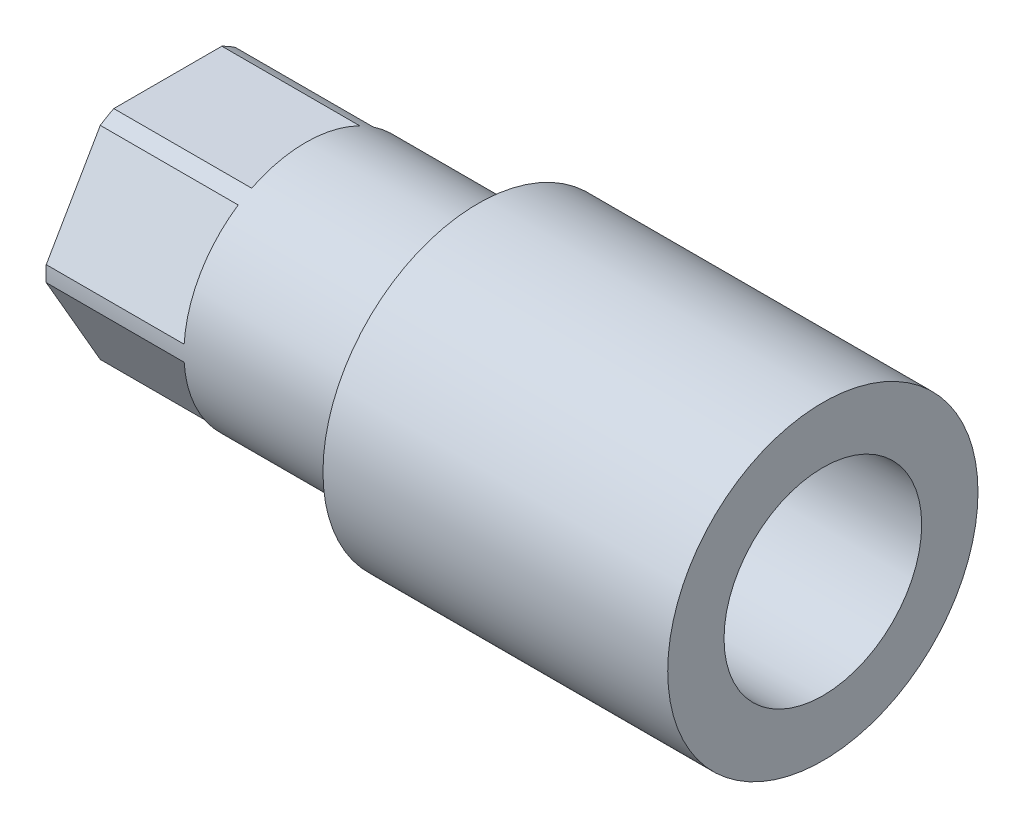
SolidWorks part; units mm, degrees
material "A286, generico"
ref_plane "Front Plane" through (0, 0, 0) normal (0, 0, 1) x (1, 0, 0)
ref_plane "Top Plane" through (0, 0, 0) normal (0, 1, 0) x (1, 0, 0)
ref_plane "Right Plane" through (0, 0, 0) normal (1, 0, 0) x (0, 0, -1)
sketch "Sketch1" plane through (0, 0, 0) normal (0, 0, 1) x (1, 0, 0)
  line L2 (57, -13.5) -> (27, -13.5)
  line L3 (27, -13.5) -> (27, -10.6)
  line L6 (27, -10.6) -> (0, -10.6)
  line L7 (0, -10.6) -> (0, -3.175)
  line L8 (0, 0) -> (57, 0) construction
  line L9 (0, -3.175) -> (34, -3.175)
  line L10 (34, -3.175) -> (34, -8.6)
  line L11 (34, -8.6) -> (57, -8.6)
  line L12 (57, -13.5) -> (57, -8.6)
  dimension "D1" = 57
  dimension "D2" = 27
  dimension "D3" = 21.2
  dimension "D4" = 17.2
  dimension "D5" = 30
  dimension "D6" = 6.35
  dimension "D7" = 23
revolve "Revolve1" add sketch "Sketch1" angle 360 about L8
sketch "Sketch2" plane through (0, 0, 0) normal (-1, 0, 0) x (0, 0, 1)
  line L1 (-5.4848, 9.5) -> (-10.9697, 0)
  line L2 (-10.9697, 0) -> (-5.4848, -9.5)
  line L3 (-5.4848, -9.5) -> (5.4848, -9.5)
  line L4 (5.4848, -9.5) -> (10.9697, 0)
  line L5 (10.9697, 0) -> (5.4848, 9.5)
  line L6 (5.4848, 9.5) -> (-5.4848, 9.5)
  circle A0 centre (0, 0) radius 9.5 construction
  circle A1 centre (0, 0) radius 10.6 construction
  circle A2 centre (0, 0) radius 10.6
  dimension "D1" = 19
extrude "Cut-Extrude2" cut sketch "Sketch2" against normal blind 12 contours L6 A1 | L1 A1 | L5 A1 | L4 A1 | L3 A1 | L2 A1 | A2
